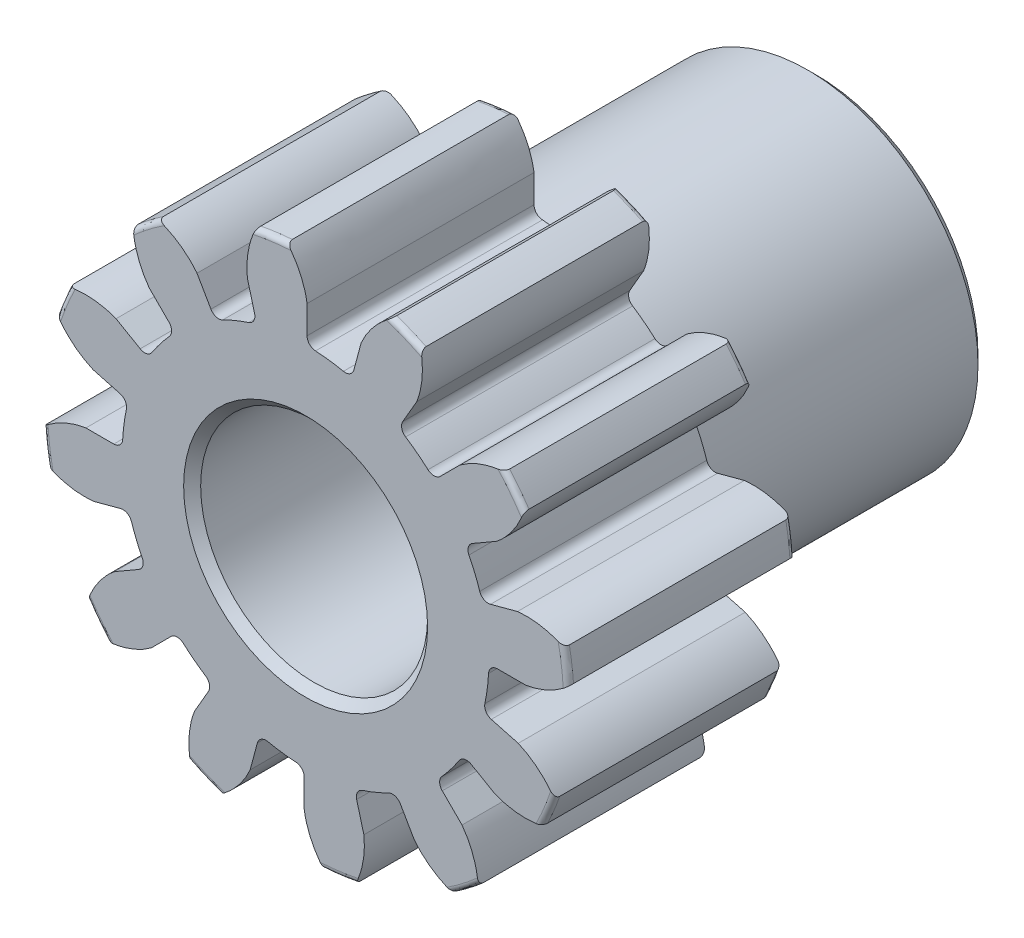
SolidWorks part; units mm, degrees
ref_plane "Front" through (0, 0, 0) normal (0, 0, 1) x (1, 0, 0)
ref_plane "Top" through (0, 0, 0) normal (0, 1, 0) x (1, 0, 0)
ref_plane "Right" through (0, 0, 0) normal (1, 0, 0) x (0, 0, -1)
sketch "Sketch1" plane through (0, 0, 0) normal (0, 0, 1) x (1, 0, 0)
  line L0 (-152.4, 0) -> (152.4, 0) construction
  circle A0 centre (0, 0) radius 7.366
  circle A1 centre (0, 0) radius 6.35 construction
  circle A3 centre (0, 0) radius 5.1255 construction
  dimension "D1" = 1.2245
  dimension "D2" = 2.2405
  dimension "D3" = 1.016
extrude "Boss-Extrude1" add sketch "Sketch1" against normal blind 6.35
sketch "Sketch2" plane through (0, 0, 0) normal (1, 0, 0) x (0, 0, -1)
  line L0 (6.35, 0) -> (14.2875, 0)
  line L1 (6.35, 0) -> (6.35, 4.7625)
  line L2 (6.35, 4.7625) -> (14.2875, 4.7625)
  line L3 (14.2875, 4.7625) -> (14.2875, 0)
  point P5 (14.2875, -4.7625)
  point P6 (0, -7.366)
  point P7 (6.35, -7.366)
  point P9 (0, 7.366)
revolve "Revolve1" add sketch "Sketch2" angle 360 mid plane about L0
fillet "Fillet2" radius 0.1473 3 edges at (7.366, 0, -6.35) (7.366, 0, 0) (4.7625, 0, -6.35)
sketch "Sketch3" plane through (0, 0, 0) normal (0, 0, 1) x (1, 0, 0)
  line L0 (0, 0) -> (0, 7.366) construction
  line L1 (-1.5393, 5.9519) -> (0, 6.35)
  line L2 (-9.5921, 6.35) -> (9.5921, 6.35) construction
  line L3 (-9.2865, 3.9483) -> (9.2865, 8.7517) construction
  line L4 (-1.5393, 5.9519) -> (0, 0) construction
  line L5 (-3.8025, 4.8307) -> (0, 0) construction
  line L6 (-3.8025, 4.8307) -> (-0.5543, 7.3875) construction
  line L7 (-1.0733, 6.0533) -> (0, 0) construction
  line L8 (-1.0733, 6.0533) -> (0.0225, 6.2476) construction
  arc A0 (-1.5393, 5.9519) -> (-3.8025, 4.8307) centre (0, 0) ccw
  circle A1 centre (0, 0) radius 6.35 construction
  circle A2 centre (0, 0) radius 6.1477 construction
  arc A3 (-1.5393, 5.9519) -> (-1.0733, 6.0533) centre (0, 0) cw
  circle A4 centre (0, 0) radius 7.366 construction
  point P6 (0, 6.35)
  dimension "D1" = 1.5899
  dimension "D3" = 4.1338
  dimension "D5" = 1.1129
  dimension "D2" = 2.5439
  dimension "D4" = 0.477
sketch "Sketch4" plane through (0, 0, 0) normal (0, 0, 1) x (1, 0, 0)
  line L0 (0, 0) -> (0.8218, 6.2418) construction
  line L1 (0.04, 6.1476) -> (0.04, 5.1254)
  line L2 (0, 6.35) -> (1.6435, 6.1336) construction
  line L3 (1.5525, 5.9485) -> (1.2879, 4.9611)
  line L4 (0.04, 5.1254) -> (0, 0) construction
  line L5 (0, 0) -> (0, 7.366) construction
  line L6 (-3.8025, 4.8307) -> (-0.5543, 7.3875) construction
  line L7 (-3.8025, 4.8307) -> (-0.5543, 7.3875) construction
  arc A0 (1.2879, 4.9611) -> (0.04, 5.1254) centre (0, 0) ccw
  arc A1 (0, 6.35) -> (1.6435, 6.1336) centre (0, 0) cw construction
  circle A2 centre (0, 0) radius 6.35 construction
  circle A3 centre (0, 0) radius 6.1477 construction
  circle A4 centre (0, 0) radius 5.1255 construction
  arc A5 (2.4475, 6.9923) -> (-0.5543, 7.3875) centre (0, 0) ccw
  spline S0 degree 2 poles (-0.5543, 7.3875) (-0.0642, 6.8316) (0.04, 6.1476) knots 0 0 0 1 1 1
  spline S1 degree 2 poles (2.4475, 6.9923) (1.8302, 6.5822) (1.5525, 5.9485) knots 0 0 0 1 1 1
  dimension "D1" = 1.6624
extrude "Cut-Extrude1" cut sketch "Sketch4" against normal through all
fillet "Fillet1" radius 0.2494 2 edges at (1.2879, 4.9611, -3.175) (0.04, 5.1254, -3.175)
pattern_circular "CirPattern1" count 12 over 360 about axis through (0, 0, -6.35) along (0, 0, 1) of "Cut-Extrude1", "Fillet1"
sketch "Sketch5" plane through (0, 0, 0) normal (0, 0, 1) x (1, 0, 0)
  circle A0 centre (0, 0) radius 3.175
  circle A1 centre (0, 0) radius 3.175 construction
  dimension "Bore Min" = 6.35
  dimension "Bore Max" = 6.35
extrude "Cut-Extrude2" cut sketch "Sketch5" against normal through all
chamfer "Chamfer1" distance 0.2381 angle 45 3 edges at (4.7625, 0, -14.2875) (3.175, 0, 0) (3.175, 0, -14.2875)
sketch "Pitch Dia" plane through (0, 0, 0) normal (0, 0, 1) x (1, 0, 0)
  circle A0 centre (0, 0) radius 6.35 construction
  circle A1 centre (0, 0) radius 6.35
equation "\"D1@Boss-Extrude1\" = \"Face Wd@Sketch2\""
equation "\"D2@Sketch3\" = \"D1@Sketch3\"*1.6"
equation "\"D3@Sketch3\" = \"D1@Sketch3\"+\"D2@Sketch3\""
equation "\"D4@Sketch3\" = \"D1@Sketch3\"*.3"
equation "\"D5@Sketch3\" = \"D1@Sketch3\"-\"D4@Sketch3\""
equation "\"D1@Sketch4\" = 1.5708/(\"Number of Teeth@Sketch1\"/\"Ptich Dia@Sketch1\")"
equation "\"D1@Chamfer1\" = \"B Hub Dia@Sketch2\"*.025"
equation "\"D1@CirPattern1\" = \"Number of Teeth@Sketch1\""
equation "\"D1@Fillet1\" = \"D1@Sketch4\"*.15"
equation "\"D1@Fillet2\" = \"OD@Sketch1\"*.01"
equation "\"D1@Sketch1\" = 1.157/(\"Number of Teeth@Sketch1\"/\"Ptich Dia@Sketch1\")"
